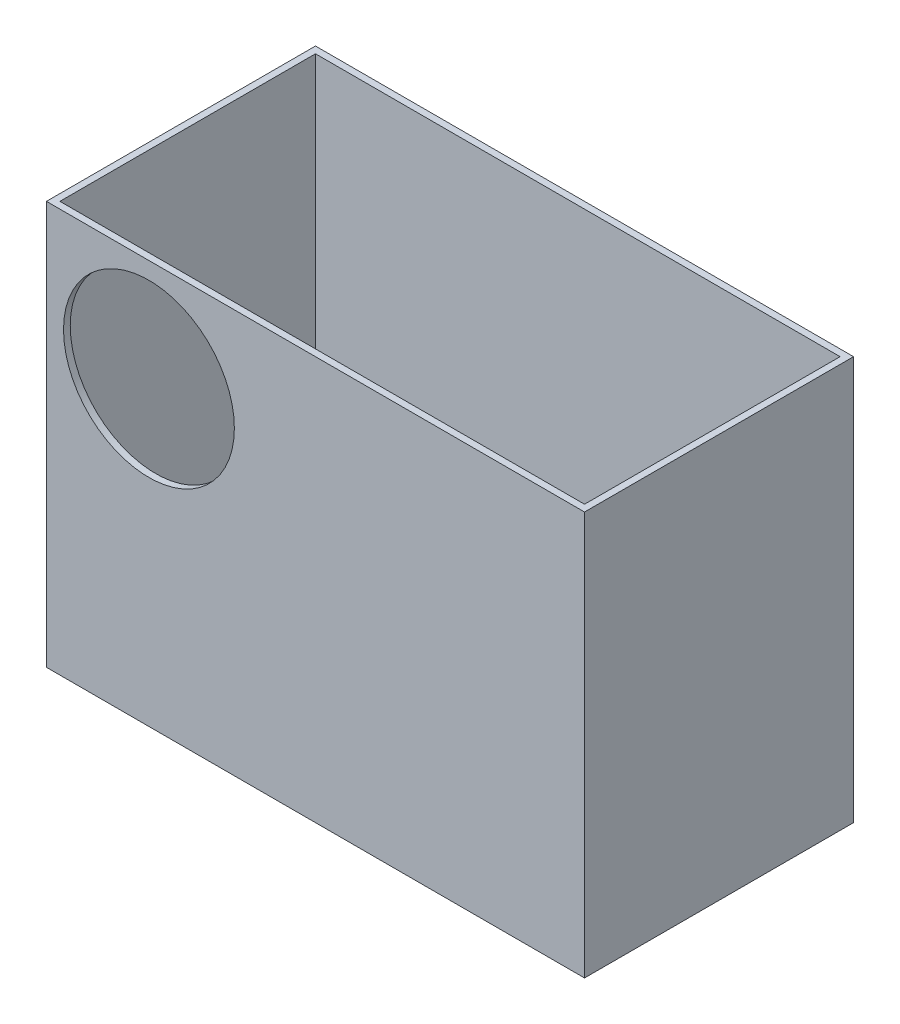
SolidWorks part; units mm, degrees
ref_plane "Frontal Plane" through (0, 0, 0) normal (0, 0, 1) x (1, 0, 0)
ref_plane "Horizontal Plane" through (0, 0, 0) normal (0, 1, 0) x (1, 0, 0)
ref_plane "Profile Plane" through (0, 0, 0) normal (1, 0, 0) x (0, 0, -1)
sketch "Sketch1" plane through (0, 0, 0) normal (0, 1, 0) x (1, 0, 0)
  line L1 (-195, -95) -> (195, -95)
  line L2 (-195, -95) -> (-195, 95)
  line L3 (-195, 95) -> (195, 95)
  line L4 (195, -95) -> (195, 95)
  line L5 (-195, -95) -> (195, 95) construction
  line L6 (-195, 95) -> (195, -95) construction
  line L7 (-200, -100) -> (200, -100)
  line L8 (-200, -100) -> (-200, 100)
  line L9 (-200, 100) -> (200, 100)
  line L10 (200, -100) -> (200, 100)
  line L11 (-200, -100) -> (200, 100) construction
  line L12 (-200, 100) -> (200, -100) construction
  point P0 (0, 0)
  point P6 (0, 0)
  dimension "D1" = 5
  dimension "D2" = 5
  dimension "D3" = 400
  dimension "D4" = 200
extrude "Boss-Extrude1" add sketch "Sketch1" along normal blind 300
sketch "Sketch7" plane through (0, 0, 100) normal (0, 0, 1) x (1, 0, 0)
  line L0 (-200, 300) -> (200, 300) construction
  line L1 (-200, 300) -> (-200, 0) construction
  circle A0 centre (-123.8, 223.8) radius 63.5
  dimension "D1" = 127
  dimension "D2" = 76.2
  dimension "D3" = 76.2
extrude "Cut-Extrude1" cut sketch "Sketch7" against normal up to next
sketch "Sketch8" plane through (0, 0, 0) normal (0, -1, 0) x (1, 0, 0)
  line L1 (-200, -100) -> (200, -100)
  line L2 (-200, -100) -> (-200, 100)
  line L3 (-200, 100) -> (200, 100)
  line L4 (200, -100) -> (200, 100)
  line L5 (-200, -100) -> (200, 100) construction
  line L6 (-200, 100) -> (200, -100) construction
  point P0 (0, 0)
extrude "Boss-Extrude2" add sketch "Sketch8" against normal blind 0.5
equation "\"D1@Sketch1\"=\"WallThickness\""
equation "\"D2@Sketch1\"=\"WallThickness\""
equation "\"D3@Sketch1\"=\"Box-X\""
equation "\"PinDiameter\"= 0"
equation "\"WallThickness\"= 0.5cm"
equation "\"Box-X\"= 40cm"
equation "\"Box-Z\"= 20cm"
equation "\"BottomPlateX\"= 3ft"
equation "\"ArmPlateX\"= 18in"
equation "\"Arm1X\"= 5cm"
equation "\"Arm1L\"= 60cm"
equation "\"Arm2GAP\"= 5cm"
equation "\"Arm2L\"= 60cm"
equation "\"Arm2H\"= 5cm"
equation "\"Arm2Extension\"= 5cm"
equation "\"Arm3GAP\"= 5cm"
equation "\"Arm3L\"= 60cm"
equation "\"Arm3H\"= 5cm"
equation "\"Pin1-2L\"= \"Arm2GAP\" + (2 * \"WallThickness\")"
equation "\"Pin2-3L\"= \"Arm3GAP\" + (4 * \"WallThickness\")"
equation "\"D4@Sketch1\"=\"Box-Z\""
equation "\"Box-Y\"= 30cm"
equation "\"D1@Boss-Extrude1\"=\"Box-Y\""
equation "\"ActuatorL\"= 35cm"
equation "\"ArmPlateThickness\"= .125in"
equation "\"DCMotor1D\"= 65mm"
equation "\"DCMotor2X\"= 68mm"
equation "\"DCMotor2D\"= 65mm"
equation "\"DCMotor2L\"= 208mm"
equation "\"DCMotor2ShaftL\"= 39mm"
equation "\"BenchDepth\"= 5cm"
equation "\"BenchH\"= 10cm"
equation "\"BenchL\"= 15cm"
equation "\"DCMotor1L\"= 215mm"
equation "\"DCMotor1ShaftL\"= 30mm"
equation "\"BottomPlateZ\"= 2ft"
equation "\"BottomPlateHoleD\"=((\"ArmPlateX\")^2+(\"ArmPlateDepth\")^2)^.5+ 10mm"
equation "\"ActuatorPinD\"= 6.35mm"
equation "\"ActuatorPinL\"= 15cm"
equation "\"ArmPlateDepth\"= 7.1875in"
equation "\"DCMotor2ShaftD\"= 15mm"
equation "\"PillowBlockW\"= 5cm"
equation "\"PillowBlockCenterH\"= \"DCMotor2X\"/2"
equation "\"EncoderRadius\"= 19mm"
equation "\"EncoderShaftL\"= 15mm"
equation "\"EncoderL\"= 33mm"
equation "\"EncoderHousingThickness\"= 7.5mm"
equation "\"TurntableID\"= 70mm"
equation "\"TurntableInner2*t\" = (\"TurntableOD\"-\"TurntableID\")*.25 - 1mm"
equation "\"TurntableInnerHoleRadius\"= \"TurntableID\"*.5 + \"TurntableInner2*t\"*.5"
equation "\"TurntableOD\"= 120mm"
equation "\"TurntableOuterHoleRadius\" = \"TurntableOD\"*.5 - ((\"TurntableOD\"-\"TurntableID\")*.25-.5mm)*.5"
equation "\"4040Height\"= 30cm"
equation "\"RotaryUnionThickness\"= 1cm"
equation "\"D1\" = \"BenchL\""
equation "\"D1@Boss-Extrude3\"=\"BenchL\""
equation "\"D4@Sketch4\"=\"BenchH\""
equation "\"D3@Sketch4\"=\"BenchDepth\""
equation "\"D2@Sketch4\"=\"WallThickness\""
equation "\"D1@Sketch4\"=\"WallThickness\""
